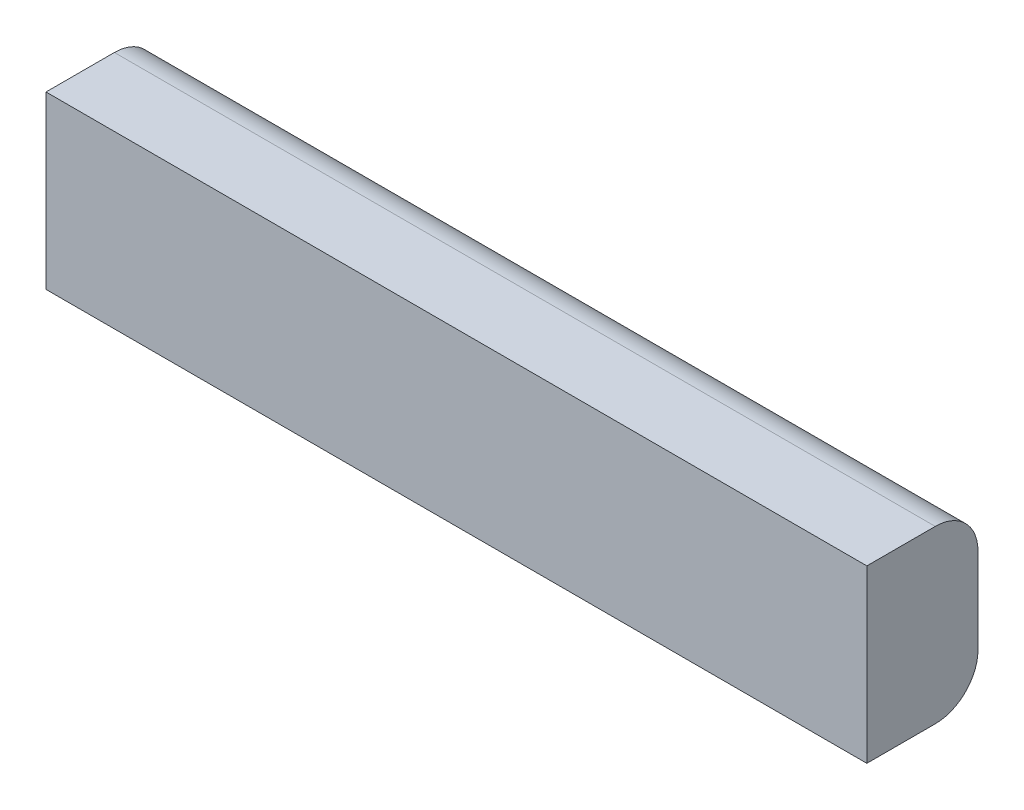
SolidWorks part; units mm, degrees
ref_plane "Front Plane" through (0, 0, 0) normal (0, 0, 1) x (1, 0, 0)
ref_plane "Top Plane" through (0, 0, 0) normal (0, 1, 0) x (1, 0, 0)
ref_plane "Right Plane" through (0, 0, 0) normal (1, 0, 0) x (0, 0, -1)
sketch "Sketch1" plane through (0, 0, 0) normal (1, 0, 0) x (0, 0, -1)
  line L1 (49.3736, 66.0217) -> (-1.4264, 66.0217)
  line L2 (81.1236, 34.2717) -> (81.1236, -29.2283)
  line L3 (49.3736, -60.9783) -> (-1.4264, -60.9783)
  line L4 (-1.4264, 66.0217) -> (-1.4264, -60.9783)
  arc A0 (49.3736, 66.0217) -> (81.1236, 34.2717) centre (49.3736, 34.2717) cw
  arc A1 (81.1236, -29.2283) -> (49.3736, -60.9783) centre (49.3736, -29.2283) cw
  point P8 (81.1236, -60.9783)
  dimension "D3" = 31.75
  dimension "D1" = 127
extrude "Boss-Extrude1" add sketch "Sketch1" along normal mid plane 609.6
equation "\"bumple\"= 24in'bumpler length"
equation "\"D1@Boss-Extrude1\"=\"bumple\""
